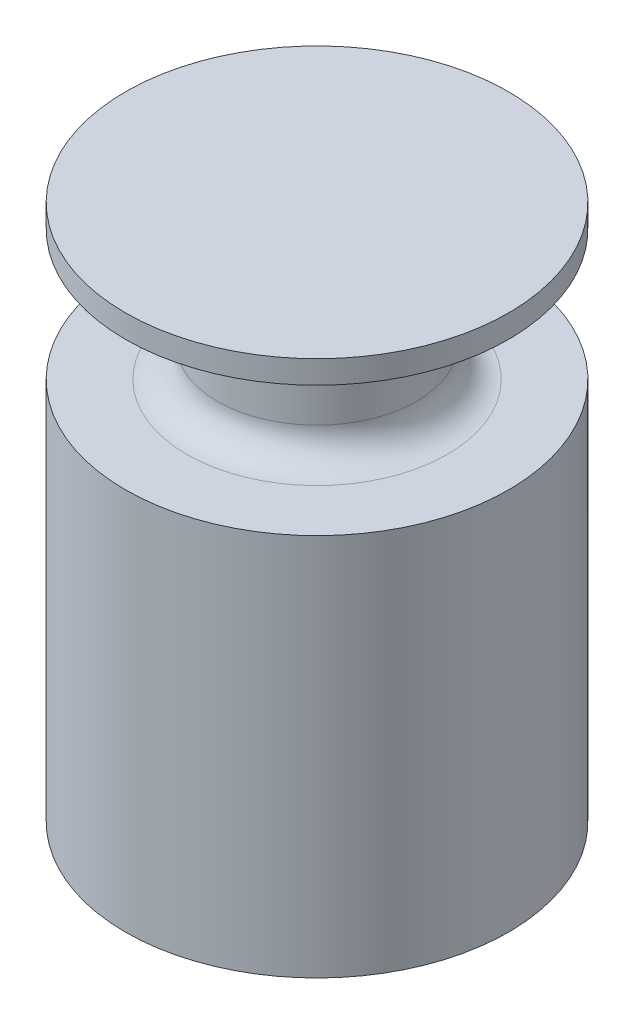
SolidWorks part; units mm, degrees
ref_plane "Front Plane" through (0, 0, 0) normal (0, 0, 1) x (1, 0, 0)
ref_plane "Top Plane" through (0, 0, 0) normal (0, 1, 0) x (1, 0, 0)
ref_plane "Right Plane" through (0, 0, 0) normal (1, 0, 0) x (0, 0, -1)
sketch "Sketch1" plane through (0, 0, 0) normal (0, 1, 0) x (1, 0, 0)
  circle A0 centre (0, 0) radius 25
  dimension "D1" = 50
extrude "Boss-Extrude1" add sketch "Sketch1" along normal blind 70
ref_plane "Plane1" through (0, 67, 0) normal (0, 1, 0) x (1, 0, 0)
sketch "Sketch2" plane through (0, 67, 0) normal (0, 1, 0) x (1, 0, 0)
  circle A0 centre (0, 0) radius 13
  circle A1 centre (0, 0) radius 25 construction
  dimension "D1" = 12
extrude "Cut-Extrude1" cut sketch "Sketch2" against normal blind 17 flip side to cut
fillet "Fillet1" radius 4 2 edges at (0, 50, 13) (0, 67, 13)
